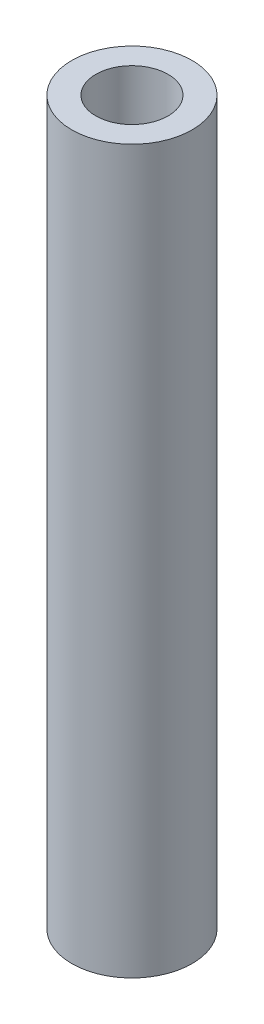
SolidWorks part; units mm, degrees
material "7050-T73510"
ref_plane "前视基准面" through (0, 0, 0) normal (0, 0, 1) x (1, 0, 0)
ref_plane "上视基准面" through (0, 0, 0) normal (0, 1, 0) x (1, 0, 0)
ref_plane "右视基准面" through (0, 0, 0) normal (1, 0, 0) x (0, 0, -1)
sketch "草图1" plane through (0, 0, 0) normal (0, 1, 0) x (1, 0, 0)
  circle A0 centre (0, 0) radius 2.5
  circle A1 centre (0, 0) radius 1.5
  dimension "D1" = 3
  dimension "D2" = 5
extrude "凸台-拉伸1" add sketch "草图1" along normal blind 30
